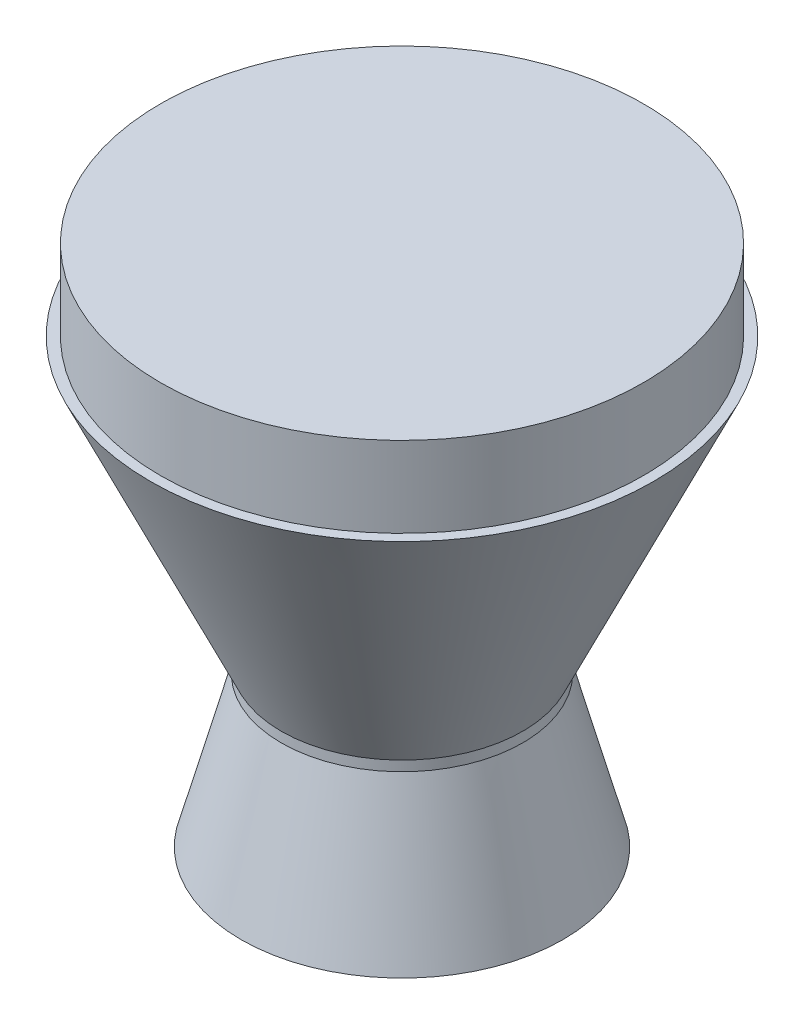
SolidWorks part; units mm, degrees
ref_plane "Front Plane" through (0, 0, 0) normal (0, 0, 1) x (1, 0, 0)
ref_plane "Top Plane" through (0, 0, 0) normal (0, 1, 0) x (1, 0, 0)
ref_plane "Right Plane" through (0, 0, 0) normal (1, 0, 0) x (0, 0, -1)
sketch "Sketch1" plane through (0, 0, 0) normal (1, 0, 0) x (0, 0, -1)
  line L0 (0, 0) -> (0, -164.872)
  line L1 (0, -164.872) -> (50.8, -164.872)
  line L2 (50.8, -164.872) -> (38.1, -117.475)
  line L3 (38.1, -117.475) -> (38.1, -114.3)
  line L4 (38.1, -114.3) -> (79.375, -25.4)
  line L5 (79.375, -25.4) -> (76.2, -25.4)
  line L6 (76.2, -25.4) -> (76.2, 0)
  line L7 (76.2, 0) -> (0, 0)
  point P3 (0, 0)
  point P10 (0, 157.0441)
  point P11 (0, 182.2686)
  point P12 (92.5185, 118.9857)
  point P13 (70.1354, 93.269)
  point P14 (38.1, 66.6219)
  point P15 (79.375, 88.8846)
  point P16 (79.375, 123.3124)
  point P17 (50.8, -91.6422)
  point P18 (38.1, -66.0961)
  point P19 (38.1, -179.4404)
  point P20 (38.1, -102.2419)
  point P21 (38.1, -83.7792)
  point P22 (38.1, -79.4332)
  point P23 (38.1, -106.4436)
  dimension "D1" = 76.2
  dimension "D2" = 50.8
  dimension "D3" = 3.175
  dimension "D4" = 38.1
  dimension "D5" = 15
  dimension "D6" = 3.175
  dimension "D7" = 114.3
  dimension "D8" = 25.4
revolve "Revolve1" add sketch "Sketch1" angle 360 about L0
shell "Shell1" thickness 3.175
